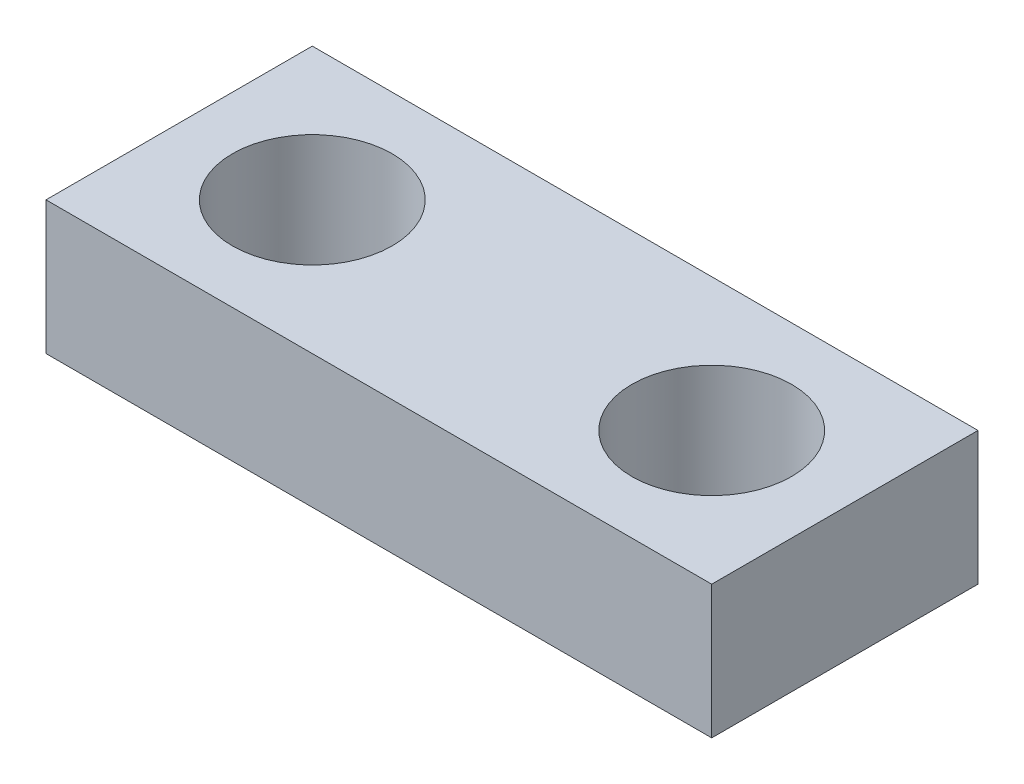
SolidWorks part; units mm, degrees
ref_plane "Front Plane" through (0, 0, 0) normal (0, 0, 1) x (1, 0, 0)
ref_plane "Top Plane" through (0, 0, 0) normal (0, 1, 0) x (1, 0, 0)
ref_plane "Right Plane" through (0, 0, 0) normal (1, 0, 0) x (0, 0, -1)
sketch "Sketch1" plane through (0, 0, 0) normal (0, 1, 0) x (1, 0, 0)
  line L1 (12.5, 5) -> (-12.5, 5)
  line L2 (12.5, 5) -> (12.5, -5)
  line L3 (12.5, -5) -> (-12.5, -5)
  line L4 (-12.5, 5) -> (-12.5, -5)
  line L5 (12.5, 5) -> (-12.5, -5) construction
  line L6 (12.5, -5) -> (-12.5, 5) construction
  circle A0 centre (-7.5, 0) radius 3
  circle A1 centre (7.5, 0) radius 3
  point P0 (0, 0)
  dimension "D3" = 6
  dimension "D1" = 10
  dimension "D2" = 25
  dimension "D4" = 5
  dimension "D5" = 5
  dimension "D6" = 15
extrude "Boss-Extrude1" add sketch "Sketch1" along normal mid plane 5
equation "\"D2@Sketch1\"= \"D6@Sketch1\" + 10mm"
